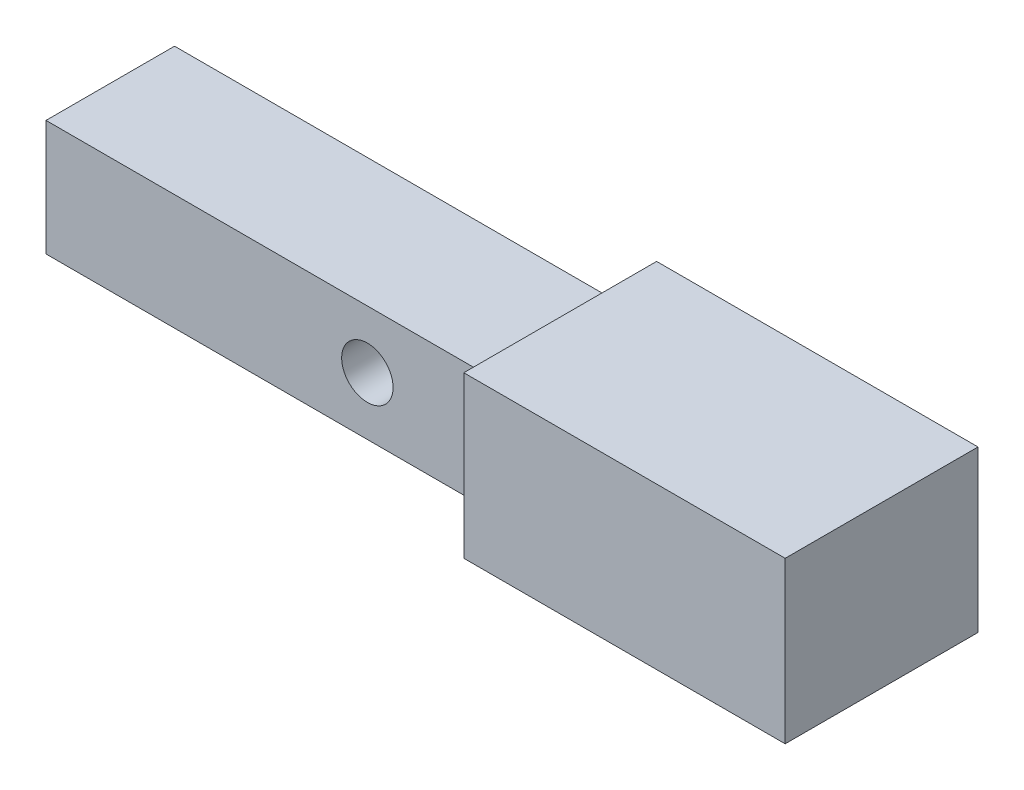
SolidWorks part; units mm, degrees
ref_plane "Front Plane" through (0, 0, 0) normal (0, 0, 1) x (1, 0, 0)
ref_plane "Top Plane" through (0, 0, 0) normal (0, 1, 0) x (1, 0, 0)
ref_plane "Right Plane" through (0, 0, 0) normal (1, 0, 0) x (0, 0, -1)
sketch "Sketch1" plane through (0, 0, 0) normal (0, 0, 1) x (1, 0, 0)
  line L0 (0, 9) -> (-50, 9)
  line L1 (-50, 9) -> (-50, -9)
  line L2 (-50, -9) -> (0, -9)
  line L4 (50, 9) -> (0, 9)
  line L5 (50, 9) -> (50, -9)
  line L6 (50, -9) -> (0, -9)
  line L7 (0, 9) -> (0, -9)
  circle A0 centre (0, 0) radius 4
  arc A1 (0, -9) -> (0, 9) centre (0, 0) ccw
  point P11 (20.4365, -24.3177)
  point P12 (0, 0)
  dimension "D1" = 8
  dimension "D2" = 5
  dimension "D3" = 50
  dimension "D4" = 50
extrude "Boss-Extrude1" add sketch "Sketch1" along normal blind 20 contours A1 L6 L5 L4 | A0 L7 L0 L1 L2 | L7 A1 A0
ref_plane "Plane1" through (0, 0, 10) normal (0, 0, 1) x (1, 0, 0)
sketch "Sketch2" plane through (0, 0, 10) normal (0, 0, 1) x (1, 0, 0)
  line L1 (20, -12.5) -> (70, -12.5)
  line L2 (20, -12.5) -> (20, 12.5)
  line L3 (20, 12.5) -> (70, 12.5)
  line L4 (70, -12.5) -> (70, 12.5)
  point P4 (20, 0)
  dimension "D1" = 20
  dimension "D2" = 25
  dimension "D3" = 50
extrude "Boss-Extrude2" add sketch "Sketch2" along normal mid plane 30
